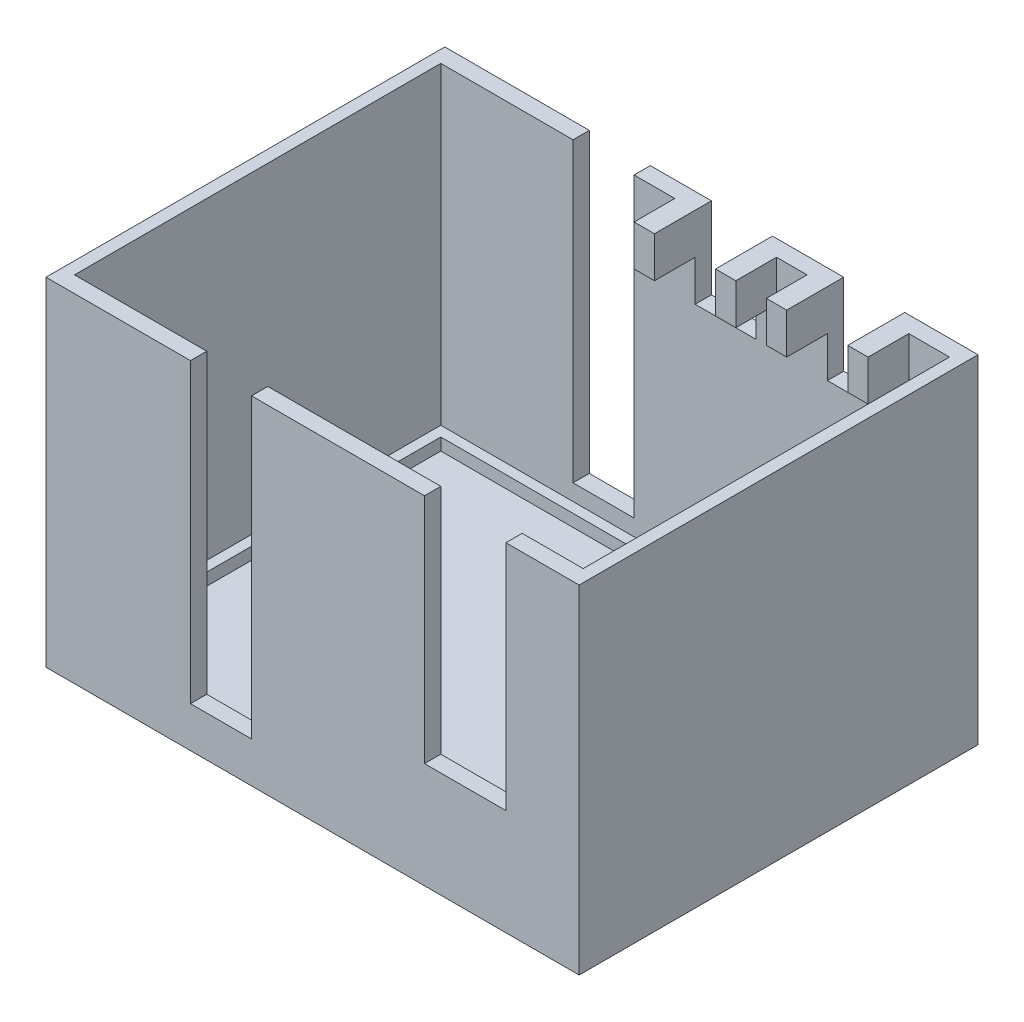
SolidWorks part; units mm, degrees
ref_plane "Front Plane" through (0, 0, 0) normal (0, 0, 1) x (1, 0, 0)
ref_plane "Top Plane" through (0, 0, 0) normal (0, 1, 0) x (1, 0, 0)
ref_plane "Right Plane" through (0, 0, 0) normal (1, 0, 0) x (0, 0, -1)
sketch "Sketch1" plane through (0, 0, 0) normal (0, 1, 0) x (1, 0, 0)
  line L1 (62.5, -45) -> (-62.5, -45)
  line L2 (62.5, -45) -> (62.5, 45)
  line L3 (62.5, 45) -> (-62.5, 45)
  line L4 (-62.5, -45) -> (-62.5, 45)
  line L5 (62.5, -45) -> (-62.5, 45) construction
  line L6 (62.5, 45) -> (-62.5, -45) construction
  line L7 (65.5, -49) -> (-65.5, -49)
  line L8 (65.5, -49) -> (65.5, 49)
  line L9 (65.5, 49) -> (-65.5, 49)
  line L10 (-65.5, -49) -> (-65.5, 49)
  line L11 (65.5, -49) -> (-65.5, 49) construction
  line L12 (65.5, 49) -> (-65.5, -49) construction
  point P0 (0, 0)
  point P5 (0, 0)
  dimension "D4" = 4
  dimension "D1" = 125
  dimension "D2" = 90
  dimension "D3" = 3
extrude "Boss-Extrude1" add sketch "Sketch1" along normal blind 80
sketch "Sketch2" plane through (0, 0, 0) normal (0, -1, 0) x (1, 0, 0)
  line L1 (65.5, -49) -> (-65.5, -49)
  line L2 (65.5, -49) -> (65.5, 49)
  line L3 (65.5, 49) -> (-65.5, 49)
  line L4 (-65.5, -49) -> (-65.5, 49)
extrude "Boss-Extrude2" add sketch "Sketch2" along normal blind 3
sketch "Sketch4" plane through (0, 0, 0) normal (0, 1, 0) x (1, 0, 0)
  line L1 (-62.5, 45) -> (62.5, 45)
  line L2 (-62.5, 45) -> (-62.5, -45)
  line L3 (-62.5, -45) -> (62.5, -45)
  line L4 (62.5, 45) -> (62.5, -45)
  line L5 (59.5, -42) -> (-60, -42)
  line L6 (59.5, -42) -> (59.5, 42.5)
  line L7 (59.5, 42.5) -> (-60, 42.5)
  line L8 (-60, -42) -> (-60, 42.5)
  dimension "D1" = 2.5
  dimension "D2" = 2.5
  dimension "D3" = 3
  dimension "D4" = 3
extrude "Boss-Extrude3" add sketch "Sketch4" along normal blind 3
sketch "Sketch5" plane through (0, 0, -49) normal (0, 0, -1) x (-1, 0, 0)
  line L0 (-65.5, 80) -> (65.5, 80) construction
  line L1 (15, 80) -> (30, 80)
  line L2 (15, 80) -> (15, 7)
  line L3 (15, 7) -> (30, 7)
  line L4 (30, 80) -> (30, 7)
  line L5 (15, 80) -> (30, 7) construction
  line L6 (15, 7) -> (30, 80) construction
  line L7 (62.5, 74.3372) -> (62.5, 12.8298) construction
  line L8 (65.5, 80) -> (65.5, -3) construction
  line L9 (65.5, -3) -> (-65.5, -3) construction
  point P0 (22.5, 43.5)
  dimension "D1" = 3
  dimension "D2" = 40
  dimension "D3" = 15
  dimension "D4" = 10
extrude "Cut-Extrude1" cut sketch "Sketch5" against normal through all
sketch "Sketch6" plane through (0, 0, 45) normal (0, 0, -1) x (-1, 0, 0)
  line L0 (15, 80) -> (-62.5, 80) construction
  line L1 (-27.5, 23) -> (-47.5, 23)
  line L2 (-27.5, 23) -> (-27.5, 80)
  line L3 (-27.5, 80) -> (-47.5, 80)
  line L4 (-47.5, 23) -> (-47.5, 80)
  line L5 (-27.5, 23) -> (-47.5, 80) construction
  line L6 (-27.5, 80) -> (-47.5, 23) construction
  line L7 (62.5, 3) -> (-62.5, 3) construction
  line L8 (-62.5, 80) -> (-62.5, 3) construction
  point P0 (-37.5, 51.5)
  dimension "D1" = 20
  dimension "D2" = 20
  dimension "D3" = 25
extrude "Cut-Extrude2" cut sketch "Sketch6" against normal up to next
sketch "Sketch7" plane through (0, 0, -45) normal (0, 0, 1) x (1, 0, 0)
  line L0 (62.5, 80) -> (-15, 80) construction
  line L1 (32.5, 80) -> (47.5, 80)
  line L2 (32.5, 80) -> (32.5, 60)
  line L3 (32.5, 60) -> (47.5, 60)
  line L4 (47.5, 80) -> (47.5, 60)
  line L6 (0, 80) -> (15, 80)
  line L7 (0, 80) -> (0, 60)
  line L8 (0, 60) -> (15, 60)
  line L9 (15, 80) -> (15, 60)
  dimension "D1" = 20
  dimension "D2" = 15
  dimension "D3" = 15
  dimension "D4" = 15
extrude "Cut-Extrude3" cut sketch "Sketch7" against normal up to next
sketch "Sketch8" plane through (0, 0, -45) normal (0, 0, 1) x (1, 0, 0)
  line L1 (0, 80) -> (-5, 80)
  line L2 (0, 80) -> (0, 70)
  line L3 (0, 70) -> (-5, 70)
  line L4 (-5, 80) -> (-5, 70)
  line L5 (15, 80) -> (20, 80)
  line L6 (15, 80) -> (15, 70)
  line L7 (15, 70) -> (20, 70)
  line L8 (20, 80) -> (20, 70)
  line L9 (32.5, 80) -> (27.5, 80)
  line L10 (32.5, 80) -> (32.5, 70)
  line L11 (32.5, 70) -> (27.5, 70)
  line L12 (27.5, 80) -> (27.5, 70)
  line L13 (47.5, 80) -> (52.5, 80)
  line L14 (47.5, 80) -> (47.5, 70)
  line L15 (47.5, 70) -> (52.5, 70)
  line L16 (52.5, 80) -> (52.5, 70)
  dimension "D1" = 5
  dimension "D2" = 5
  dimension "D3" = 10
  dimension "D4" = 5
  dimension "D5" = 5
extrude "Boss-Extrude4" add sketch "Sketch8" along normal blind 10
